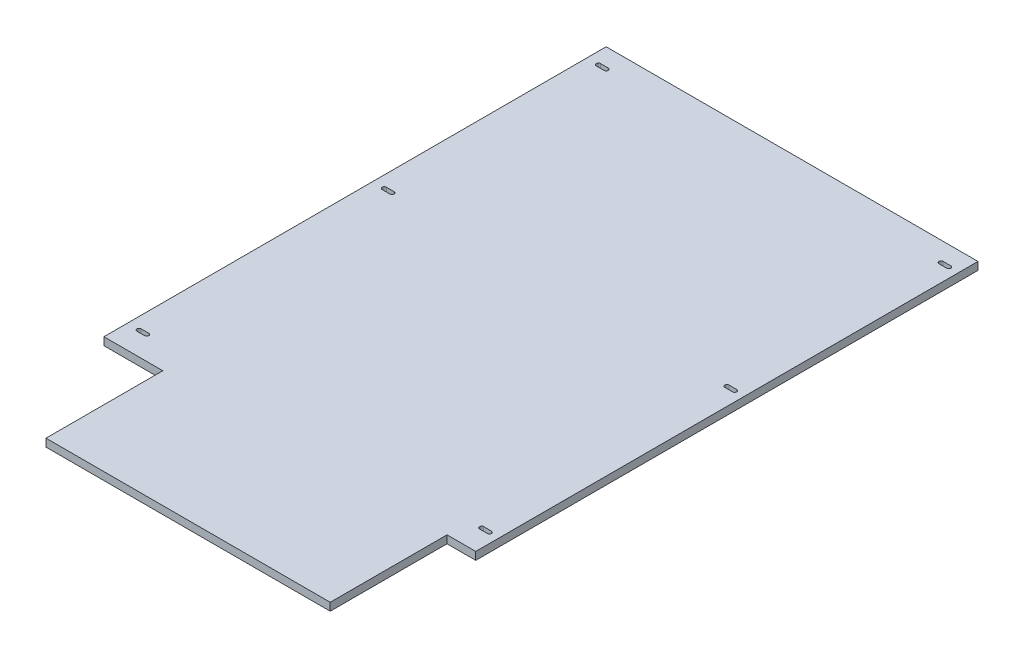
SolidWorks part; units mm, degrees
material "PE High Density"
ref_plane "Front" through (0, 0, 0) normal (0, 0, 1) x (1, 0, 0)
ref_plane "Top" through (0, 0, 0) normal (0, 1, 0) x (1, 0, 0)
ref_plane "Right" through (0, 0, 0) normal (1, 0, 0) x (0, 0, -1)
sketch "Sketch1" plane through (0, 0, 0) normal (0, 1, 0) x (1, 0, 0)
  line L0 (0, 0) -> (96.0438, 0)
  line L1 (96.0438, 0) -> (96.0438, -190.5)
  line L2 (96.0438, -190.5) -> (559.5938, -190.5)
  line L3 (559.5938, -190.5) -> (559.5938, 0)
  line L4 (559.5938, 0) -> (606.425, 0)
  line L5 (606.425, 0) -> (606.425, 819.15)
  line L6 (606.425, 819.15) -> (0, 819.15)
  line L7 (0, 819.15) -> (0, 0)
  line L8 (25.4, 0) -> (25.4, 819.15) construction
  line L9 (19.05, 38.1) -> (31.75, 38.1) construction
  line L10 (19.05, 41.4782) -> (31.75, 41.4782)
  line L11 (19.05, 34.7218) -> (31.75, 34.7218)
  line L12 (19.05, 438.15) -> (31.75, 438.15) construction
  line L13 (19.05, 441.5282) -> (31.75, 441.5282)
  line L14 (19.05, 434.7718) -> (31.75, 434.7718)
  line L15 (31.75, 787.4) -> (19.05, 787.4) construction
  line L16 (31.75, 784.0218) -> (19.05, 784.0218)
  line L17 (31.75, 790.7782) -> (19.05, 790.7782)
  line L18 (303.2125, 819.15) -> (303.2125, -190.5) construction
  line L19 (584.2, 787.4) -> (584.2, 438.15) construction
  line L20 (577.85, 787.4) -> (590.55, 787.4) construction
  line L21 (577.85, 784.0218) -> (590.55, 784.0218)
  line L22 (577.85, 790.7782) -> (590.55, 790.7782)
  line L23 (590.55, 438.15) -> (577.85, 438.15) construction
  line L24 (590.55, 441.5282) -> (577.85, 441.5282)
  line L25 (590.55, 434.7718) -> (577.85, 434.7718)
  line L26 (590.55, 38.1) -> (577.85, 38.1) construction
  line L27 (590.55, 41.4782) -> (577.85, 41.4782)
  line L28 (590.55, 34.7218) -> (577.85, 34.7218)
  line L29 (327.8187, -190.5) -> (327.8187, 819.15) construction
  line L30 (584.2, 438.15) -> (584.2, 38.1) construction
  arc A1 (19.05, 41.4782) -> (19.05, 34.7218) centre (19.05, 38.1) ccw
  arc A2 (31.75, 34.7218) -> (31.75, 41.4782) centre (31.75, 38.1) ccw
  arc A3 (19.05, 441.5282) -> (19.05, 434.7718) centre (19.05, 438.15) ccw
  arc A4 (31.75, 434.7718) -> (31.75, 441.5282) centre (31.75, 438.15) ccw
  arc A5 (31.75, 784.0218) -> (31.75, 790.7782) centre (31.75, 787.4) ccw
  arc A6 (19.05, 790.7782) -> (19.05, 784.0218) centre (19.05, 787.4) ccw
  arc A7 (577.85, 784.0218) -> (577.85, 790.7782) centre (577.85, 787.4) cw
  arc A8 (590.55, 790.7782) -> (590.55, 784.0218) centre (590.55, 787.4) cw
  arc A9 (590.55, 441.5282) -> (590.55, 434.7718) centre (590.55, 438.15) cw
  arc A10 (577.85, 434.7718) -> (577.85, 441.5282) centre (577.85, 438.15) cw
  arc A11 (590.55, 41.4782) -> (590.55, 34.7218) centre (590.55, 38.1) cw
  arc A12 (577.85, 34.7218) -> (577.85, 41.4782) centre (577.85, 38.1) cw
  point P13 (25.4, 38.1)
  point P20 (25.4, 438.15)
  point P27 (25.4, 787.4)
  point P38 (584.2, 787.4)
  point P45 (584.2, 438.15)
  point P52 (584.2, 38.1)
  dimension "D1" = 96.0438
  dimension "D2" = 46.8312
  dimension "D3" = 819.15
  dimension "D4" = 25.4
  dimension "D5" = 6.7564
  dimension "D6" = 38.1
  dimension "D7" = 12.7
  dimension "D8" = 400.05
  dimension "D9" = 349.25
  dimension "D10" = 190.5
  dimension "D11" = 463.55
  dimension "D12" = 22.225
extrude "Boss-Extrude1" add sketch "Sketch1" along normal blind 12.7
fillet "Fillet1" [suppressed] radius 6.604
fillet "Fillet2" [suppressed] radius 6.604
sketch "Sketch2" plane through (0, 12.7, 0) normal (0, 1, 0) x (1, 0, 0)
  line L1 (606.425, 0) -> (606.425, 819.15) construction
  line L3 (577.85, 438.15) -> (590.55, 438.15) construction
  line L4 (606.425, 505.867) -> (606.425, 461.873)
  line L5 (606.425, 483.87) -> (47.625, 483.87) construction
  line L6 (0, 819.15) -> (0, 0) construction
  arc A3 (600.075, 494.8685) -> (600.075, 472.8715) centre (606.425, 483.87) ccw
  arc A4 (600.075, 494.8685) -> (606.425, 505.867) centre (593.725, 505.867) ccw
  arc A5 (606.425, 461.873) -> (600.075, 472.8715) centre (593.725, 461.873) ccw
  circle A6 centre (47.625, 483.87) radius 12.7
  dimension "D1" = 25.4
  dimension "D2" = 45.72
  dimension "D3" = 47.625
extrude "Cut-Extrude1" [suppressed] cut sketch "Sketch2" against normal through all
sketch "Sketch4" plane through (0, 0, 0) normal (0, -1, 0) x (1, 0, 0)
  line L0 (0, -819.15) -> (0, 0) construction
  line L3 (327.025, -527.05) -> (327.025, -549.275) construction
  line L4 (350.8375, -527.05) -> (350.8375, -549.275)
  line L5 (303.2125, -527.05) -> (303.2125, -549.275)
  line L7 (606.425, -819.15) -> (0, -819.15) construction
  line L8 (327.025, 0) -> (327.025, -22.225) construction
  line L9 (350.8375, 0) -> (350.8375, -22.225)
  line L10 (303.2125, 0) -> (303.2125, -22.225)
  circle A0 centre (327.025, -538.1625) radius 28.575 construction
  arc A2 (350.8375, -527.05) -> (303.2125, -527.05) centre (327.025, -527.05) ccw
  arc A3 (303.2125, -549.275) -> (350.8375, -549.275) centre (327.025, -549.275) ccw
  arc A4 (350.8375, 0) -> (303.2125, 0) centre (327.025, 0) ccw
  arc A5 (303.2125, -22.225) -> (350.8375, -22.225) centre (327.025, -22.225) ccw
  point P8 (327.025, -11.1125)
  point P12 (327.025, -538.1625)
  dimension "D2" = 57.15
  dimension "D1" = 327.025
  dimension "D3" = 527.05
  dimension "D4" = 47.625
  dimension "D5" = 22.225
  dimension "D6" = 280.9875
extrude "Cut-Extrude3" [suppressed] cut sketch "Sketch4" against normal through all
sketch "Sketch5" [suppressed] plane through (0, 0, 0) normal (0, -1, 0) x (1, 0, 0)
  line L0 (327.025, -22.225) -> (327.025, -527.05) construction
  line L1 (327.025, -466.725) -> (327.025, -82.55) construction
  line L2 (320.675, -466.725) -> (320.675, -82.55)
  line L3 (333.375, -466.725) -> (333.375, -82.55)
  arc A0 (320.675, -466.725) -> (333.375, -466.725) centre (327.025, -466.725) ccw
  arc A1 (333.375, -82.55) -> (320.675, -82.55) centre (327.025, -82.55) ccw
  point P6 (327.025, -274.6375)
  dimension "D1" = 384.175
  dimension "D2" = 12.7
extrude "Cut-Extrude4" [suppressed] cut sketch "Sketch5" against normal through all
sketch "Sketch6" [suppressed] plane through (0, 0, 0) normal (0, -1, 0) x (1, 0, 0)
  line L0 (327.025, -82.55) -> (327.025, -466.725) construction
  line L1 (327.025, -274.6375) -> (354.0125, -274.6375) construction
  line L2 (354.0125, -122.2375) -> (354.0125, -427.0375) construction
  line L3 (300.0375, -122.2375) -> (300.0375, -427.0375) construction
  circle A0 centre (354.0125, -274.6375) radius 3.3782
  circle A1 centre (354.0125, -427.0375) radius 3.3782
  circle A2 centre (354.0125, -122.2375) radius 3.3782
  circle A3 centre (300.0375, -427.0375) radius 3.3782
  circle A4 centre (300.0375, -274.6375) radius 3.3782
  circle A5 centre (300.0375, -122.2375) radius 3.3782
  dimension "D2" = 6.7564
  dimension "D1" = 26.9875
  dimension "D3" = 152.4
extrude "Cut-Extrude5" [suppressed] cut sketch "Sketch6" against normal through all
sketch "Sketch7" [suppressed] plane through (0, 0, 0) normal (0, -1, 0) x (1, 0, 0)
  line L0 (599.821, -819.15) -> (6.604, -819.15) construction
  line L1 (6.604, 0) -> (89.4398, 0) construction
  line L2 (0, -812.546) -> (0, -6.604) construction
  line L3 (7.366, -819.15) -> (6.604, -819.15)
  line L4 (6.604, 0) -> (7.366, 0)
  line L5 (0, -812.546) -> (0, -6.604)
  line L6 (0.762, -6.604) -> (0.762, -812.546)
  line L7 (566.1978, 0) -> (599.821, 0) construction
  line L8 (606.425, -505.867) -> (606.425, -812.546) construction
  line L9 (606.425, -6.604) -> (606.425, -461.873) construction
  line L10 (566.1978, 0) -> (599.821, 0)
  line L11 (599.821, -819.15) -> (6.604, -819.15)
  line L12 (606.425, -505.867) -> (606.425, -812.546)
  line L13 (606.425, -6.604) -> (606.425, -461.873)
  line L14 (605.663, -504.5472) -> (605.663, -812.546)
  line L15 (605.663, -6.604) -> (605.663, -462.3309)
  arc A0 (0, -812.546) -> (6.604, -819.15) centre (6.604, -812.546) ccw construction
  arc A1 (6.604, 0) -> (0, -6.604) centre (6.604, -6.604) ccw construction
  arc A2 (0, -812.546) -> (6.604, -819.15) centre (6.604, -812.546) ccw
  arc A3 (6.604, 0) -> (0, -6.604) centre (6.604, -6.604) ccw
  arc A4 (7.366, 0) -> (0.762, -6.604) centre (7.366, -6.604) ccw
  arc A5 (0.762, -812.546) -> (7.366, -819.15) centre (7.366, -812.546) ccw
  arc A6 (599.821, -819.15) -> (606.425, -812.546) centre (599.821, -812.546) ccw construction
  arc A7 (606.425, -505.867) -> (600.075, -494.8685) centre (593.725, -505.867) ccw construction
  arc A8 (600.075, -472.8715) -> (600.075, -494.8685) centre (606.425, -483.87) ccw construction
  arc A9 (600.075, -472.8715) -> (606.425, -461.873) centre (593.725, -461.873) ccw construction
  arc A10 (606.425, -6.604) -> (599.821, 0) centre (599.821, -6.604) ccw construction
  arc A11 (599.821, -819.15) -> (606.425, -812.546) centre (599.821, -812.546) ccw
  arc A12 (606.425, -505.867) -> (600.075, -494.8685) centre (593.725, -505.867) ccw
  arc A13 (600.075, -472.8715) -> (600.075, -494.8685) centre (606.425, -483.87) ccw
  arc A14 (600.075, -472.8715) -> (606.425, -461.873) centre (593.725, -461.873) ccw
  arc A15 (606.425, -6.604) -> (599.821, 0) centre (599.821, -6.604) ccw
  arc A16 (605.663, -6.604) -> (599.059, 0) centre (599.059, -6.604) ccw
  arc A17 (599.059, -819.15) -> (605.663, -812.546) centre (599.059, -812.546) ccw
  arc A18 (605.663, -504.5472) -> (600.075, -494.8685) centre (594.487, -504.5472) ccw
  arc A19 (599.694, -473.1004) -> (605.663, -462.3309) centre (592.963, -462.3309) ccw
  dimension "D1" = 0.762
  dimension "D2" = 0.762
extrude "Cut-Extrude6" [suppressed] cut sketch "Sketch7" against normal through all contours A18 L14 A17 L11 A11 L12 A12 | A5 L6 A4 L4 A3 L5 A2 L3 | A19 A13 A14 L13 A15 L10 A16 L15
sketch "Sketch8" [suppressed] plane through (0, 0, 0) normal (0, -1, 0) x (1, 0, 0)
  line L0 (0.762, -6.604) -> (0.762, -812.546) construction
  line L1 (0.762, -6.604) -> (0.762, -812.546)
  line L2 (605.663, -6.604) -> (605.663, -462.3309) construction
  line L3 (605.663, -6.604) -> (605.663, -812.546)
  line L4 (10.287, -6.604) -> (10.287, -812.546)
  line L5 (16.891, 0) -> (7.366, 0)
  line L6 (16.891, -819.15) -> (7.366, -819.15)
  line L7 (602.488, -6.604) -> (602.488, -812.546)
  line L8 (599.059, -819.15) -> (595.884, -819.15)
  line L9 (599.059, 0) -> (595.884, 0)
  arc A0 (0.762, -812.546) -> (7.366, -819.15) centre (7.366, -812.546) ccw construction
  arc A1 (7.366, 0) -> (0.762, -6.604) centre (7.366, -6.604) ccw construction
  arc A2 (0.762, -812.546) -> (7.366, -819.15) centre (7.366, -812.546) ccw
  arc A3 (7.366, 0) -> (0.762, -6.604) centre (7.366, -6.604) ccw
  arc A4 (599.059, -819.15) -> (605.663, -812.546) centre (599.059, -812.546) ccw construction
  arc A5 (605.663, -6.604) -> (599.059, 0) centre (599.059, -6.604) ccw construction
  arc A6 (599.059, -819.15) -> (605.663, -812.546) centre (599.059, -812.546) ccw
  arc A7 (605.663, -6.604) -> (599.059, 0) centre (599.059, -6.604) ccw
  arc A8 (16.891, 0) -> (10.287, -6.604) centre (16.891, -6.604) ccw
  arc A9 (10.287, -812.546) -> (16.891, -819.15) centre (16.891, -812.546) ccw
  arc A10 (602.488, -6.604) -> (595.884, 0) centre (595.884, -6.604) ccw
  arc A11 (595.884, -819.15) -> (602.488, -812.546) centre (595.884, -812.546) ccw
  dimension "D2" = 9.525
  dimension "D4" = 3.175
  dimension "D1" = 2
  dimension "D3" = 2
extrude "Cut-Extrude7" [suppressed] cut sketch "Sketch8" against normal through all contours L1 A2 L6 A9 L4 A8 L5 A3 | L7 A11 L8 A6 L3 A7 L9 A10
fillet "Fillet3" [suppressed] radius 2.54
